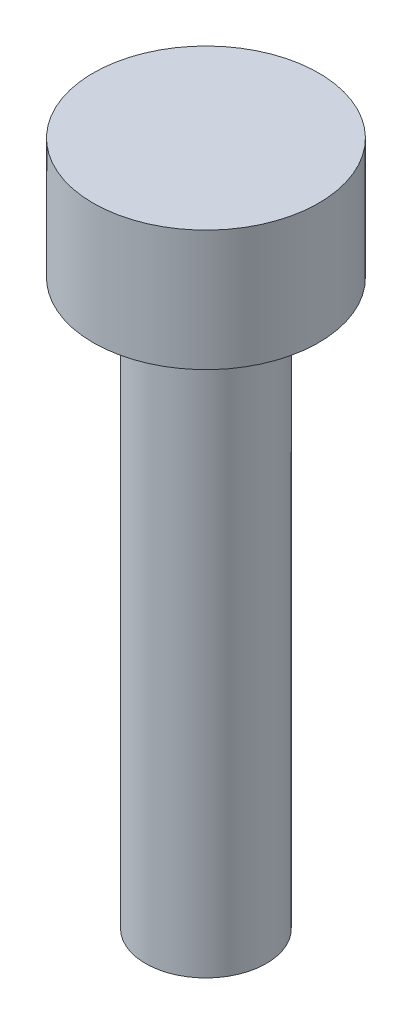
SolidWorks part; units mm, degrees
material "AISI 304"
ref_plane "前视基准面" through (0, 0, 0) normal (0, 0, 1) x (1, 0, 0)
ref_plane "上视基准面" through (0, 0, 0) normal (0, 1, 0) x (1, 0, 0)
ref_plane "右视基准面" through (0, 0, 0) normal (1, 0, 0) x (0, 0, -1)
sketch "草图1" plane through (0, 0, 0) normal (0, 1, 0) x (1, 0, 0)
  circle A0 centre (0, 0) radius 2.8
  dimension "D1" = 5.6
extrude "凸台-拉伸1" add sketch "草图1" along normal blind 3
sketch "草图2" plane through (0, 0, 0) normal (0, -1, 0) x (1, 0, 0)
  circle A0 centre (0, 0) radius 1.5
  dimension "D1" = 3
extrude "凸台-拉伸2" add sketch "草图2" along normal blind 14
